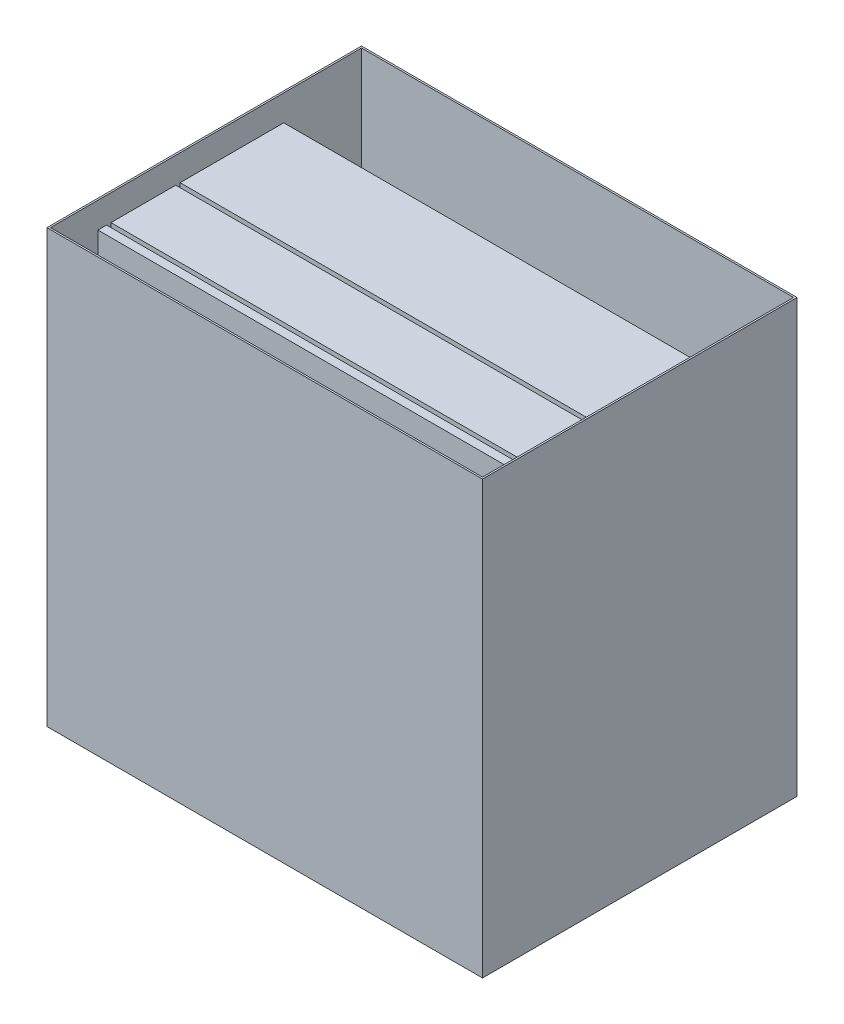
SolidWorks part; units mm, degrees
ref_plane "Front Plane" through (0, 0, 0) normal (0, 0, 1) x (1, 0, 0)
ref_plane "Top Plane" through (0, 0, 0) normal (0, 1, 0) x (1, 0, 0)
ref_plane "Right Plane" through (0, 0, 0) normal (1, 0, 0) x (0, 0, -1)
sketch "Sketch1" plane through (0, 0, 0) normal (0, 0, 1) x (1, 0, 0)
  line L1 (-304.8, 304.8) -> (304.8, 304.8)
  line L2 (-304.8, 304.8) -> (-304.8, -304.8)
  line L3 (-304.8, -304.8) -> (304.8, -304.8)
  line L4 (304.8, 304.8) -> (304.8, -304.8)
  line L5 (-304.8, 304.8) -> (304.8, -304.8) construction
  line L6 (-304.8, -304.8) -> (304.8, 304.8) construction
  point P0 (0, 0)
  dimension "D1" = 609.6
  dimension "D2" = 609.6
extrude "Boss-Extrude1" add sketch "Sketch1" along normal blind 152.4
sketch "Sketch2" plane through (0, 0, 152.4) normal (0, 0, 1) x (1, 0, 0)
  line L1 (-304.8, -304.8) -> (304.8, -304.8)
  line L2 (-304.8, -304.8) -> (-304.8, 304.8)
  line L3 (-304.8, 304.8) -> (304.8, 304.8)
  line L4 (304.8, -304.8) -> (304.8, 304.8)
  line L5 (-304.8, -304.8) -> (304.8, 304.8) construction
  line L6 (-304.8, 304.8) -> (304.8, -304.8) construction
  point P0 (0, 0)
extrude "Boss-Extrude2" add sketch "Sketch2" along normal blind 95.25 from offset 6.35 separate body
sketch "Sketch3" plane through (0, 0, 254) normal (0, 0, 1) x (1, 0, 0)
  line L1 (-304.8, -304.8) -> (304.8, -304.8)
  line L2 (-304.8, -304.8) -> (-304.8, 304.8)
  line L3 (-304.8, 304.8) -> (304.8, 304.8)
  line L4 (304.8, -304.8) -> (304.8, 304.8)
  line L5 (-304.8, -304.8) -> (304.8, 304.8) construction
  line L6 (-304.8, 304.8) -> (304.8, -304.8) construction
  point P0 (0, 0)
extrude "Boss-Extrude3" add sketch "Sketch3" along normal blind 12.7 from offset 6.35 separate body
sketch "Sketch4" plane through (0, -304.8, 0) normal (0, -1, 0) x (1, 0, 0)
  line L0 (0, 0) -> (0, 273.05) construction
  line L1 (304.8, 273.05) -> (-304.8, 273.05) construction
  line L2 (0, -126.9524) -> (0, 0) construction
  line L3 (-317.5, 330.2476) -> (317.5, 330.2476)
  line L4 (-317.5, 330.2476) -> (-317.5, -126.9524)
  line L5 (-317.5, -126.9524) -> (317.5, -126.9524)
  line L6 (317.5, 330.2476) -> (317.5, -126.9524)
  line L7 (-317.5, 330.2476) -> (317.5, -126.9524) construction
  line L8 (-317.5, -126.9524) -> (317.5, 330.2476) construction
  point P5 (0, 106.1658)
  dimension "D1" = 635
  dimension "D2" = 457.2
extrude "Extrude-Thin1" add sketch "Sketch4" against normal blind 635 separate body thin thin type one direction wall 2.54
sketch "Sketch5" plane through (0, 304.8, 0) normal (0, 1, 0) x (1, 0, 0)
  line L0 (304.8, 0) -> (304.8, -273.05)
  line L1 (304.8, 0) -> (-304.8, 0) construction
  line L2 (304.8, -152.4) -> (304.8, 0) construction
